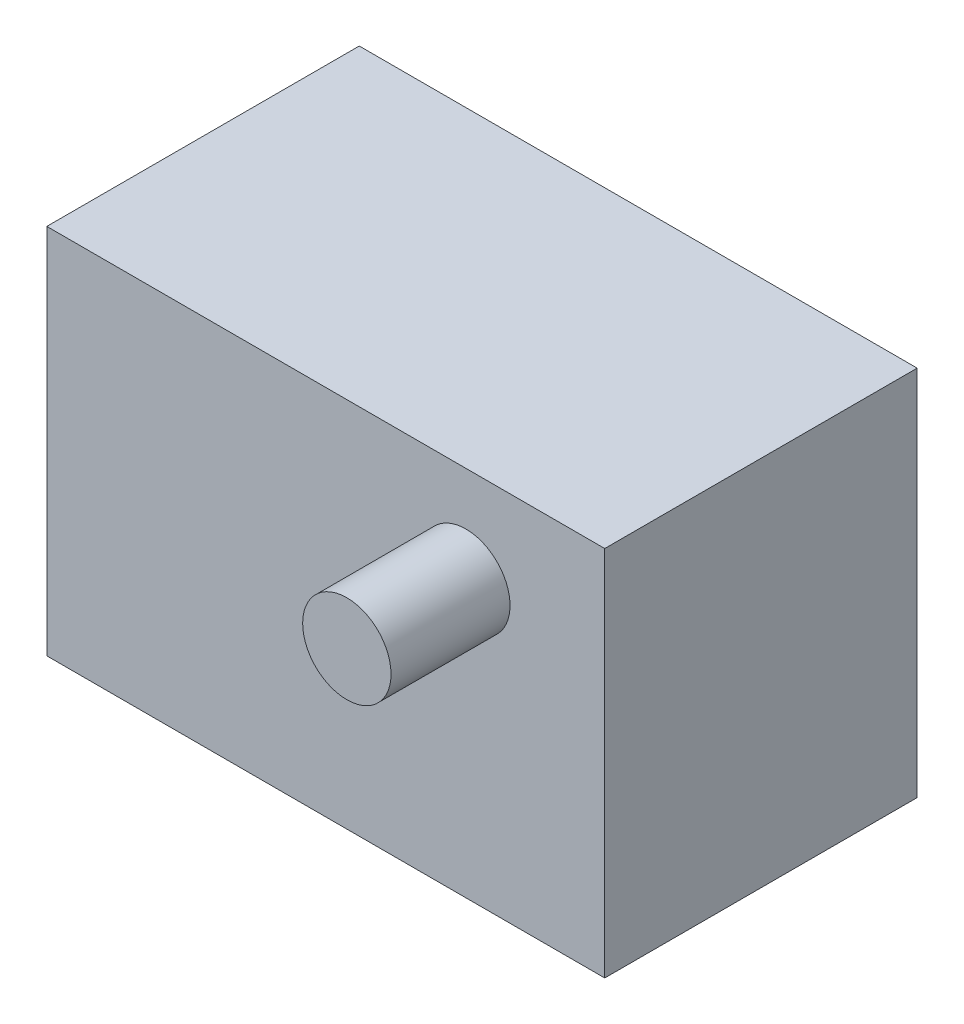
SolidWorks part; units mm, degrees
ref_plane "Alzado" through (0, 0, 0) normal (0, 0, 1) x (1, 0, 0)
ref_plane "Planta" through (0, 0, 0) normal (0, 1, 0) x (1, 0, 0)
ref_plane "Vista lateral" through (0, 0, 0) normal (1, 0, 0) x (0, 0, -1)
sketch "Croquis1" plane through (0, 0, 0) normal (0, 0, 1) x (1, 0, 0)
  line L1 (37.5, 25) -> (-37.5, 25)
  line L2 (37.5, 25) -> (37.5, -25)
  line L3 (37.5, -25) -> (-37.5, -25)
  line L4 (-37.5, 25) -> (-37.5, -25)
  line L5 (37.5, 25) -> (-37.5, -25) construction
  line L6 (37.5, -25) -> (-37.5, 25) construction
  point P0 (0, 0)
  dimension "D1" = 50
  dimension "D2" = 75
extrude "Saliente-Extruir1" add sketch "Croquis1" against normal blind 42
sketch "Croquis2" plane through (0, 0, 0) normal (0, 0, 1) x (1, 0, 0)
  line L0 (-37.5, -25) -> (37.5, -25) construction
  circle A0 centre (18.8306, 12) radius 5.9397
  point P2 (0, 0)
  dimension "D1" = 37
extrude "Saliente-Extruir2" add sketch "Croquis2" along normal blind 16
